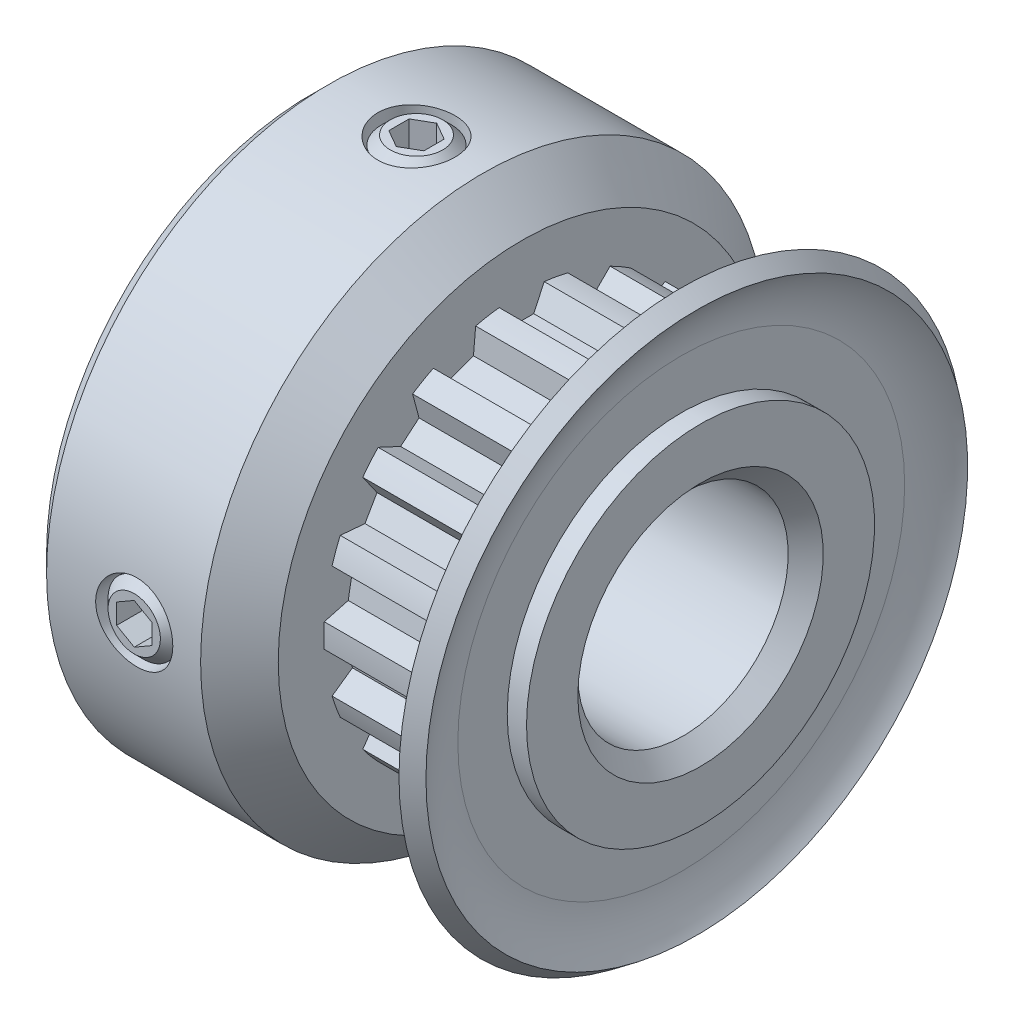
SolidWorks part; units mm, degrees
ref_plane "Front Plane" through (0, 0, 0) normal (0, 0, 1) x (1, 0, 0)
ref_plane "Top Plane" through (0, 0, 0) normal (0, 1, 0) x (1, 0, 0)
ref_plane "Right Plane" through (0, 0, 0) normal (1, 0, 0) x (0, 0, -1)
sketch "Sketch2" plane through (0, 0, 0) normal (1, 0, 0) x (0, 0, -1)
  line L3 (0, 0) -> (0, 4.9745) construction
  line L6 (0, -5.4825) -> (0, -5.8) construction
  line L7 (-0.5715, 5.4526) -> (-0.343, 4.9627)
  line L8 (0.5715, 5.4526) -> (0.343, 4.9627)
  line L9 (-0.5715, 5.4526) -> (-0.6423, 5.6046)
  line L10 (0.5715, 5.4526) -> (0.6423, 5.6046)
  line L12 (-0.343, 4.9627) -> (0.343, 4.9627)
  line L14 (0, 5.4825) -> (0, 5.8) construction
  line L15 (0, 0) -> (0, -1.143) construction
  circle A0 centre (0, 0) radius 5.8 construction
  circle A1 centre (0, 0) radius 4.9745 construction
  circle A2 centre (0, 0) radius 5.4825 construction
  arc A7 (0.6423, 5.6046) -> (-0.6423, 5.6046) centre (0, 0) ccw
  point P5 (0, 5.6412)
  dimension "D3" = 0.3175
  dimension "D1" = 50
sketch "Sketch1" plane through (0, 0, 0) normal (0, 0, 1) x (1, 0, 0)
  line L0 (-5.55, 0) -> (5.55, 0) construction
  line L1 (-5.55, 3) -> (5.55, 3)
  line L2 (-5.55, 3) -> (-5.55, 8.05)
  line L3 (-5.55, 8.05) -> (-0.657, 8.05)
  line L4 (-0.657, 8.05) -> (0.45, 6.943)
  line L5 (0.45, 6.943) -> (0.45, 5.8)
  line L6 (0.45, 5.8) -> (4.45, 5.8)
  line L7 (4.45, 5.8) -> (4.45, 6.3715)
  line L8 (4.45, 5.8) -> (5.55, 5.8) construction
  line L9 (5, 8.05) -> (5.55, 8.05)
  line L10 (5.55, 8.05) -> (5.55, 3)
  line L11 (5, 5.8) -> (5, 8.05) construction
  line L12 (-3.1035, 8.05) -> (-3.1035, 3) construction
  arc A0 (4.45, 6.3715) -> (5, 8.05) centre (7.2862, 6.3715) cw
  dimension "Bore Size" = 6
  dimension "Overall Width" = 11.1
  dimension "Inside Width" = 4
  dimension "Outside Width" = 5.1
  dimension "Hub Dia" = 16.1
  dimension "OD" = 16.1
  dimension "D1" = 45
  dimension "D2" = 11.6
  dimension "D3" = 1.143
  dimension "D4" = 0.5715
revolve "Revolve1" add sketch "Sketch1" angle 360 mid plane about L0
sketch "Sketch4" plane through (0.45, 0, 0) normal (1, 0, 0) x (0, 0, -1)
  circle A0 centre (0, 0) radius 5.6412
  circle A1 centre (0, 0) radius 5.8 construction
  circle A2 centre (0, 0) radius 5.8
extrude "Cut-Extrude2" cut sketch "Sketch4" along normal up to surface (4 mm away) up to face at (4.45, 0, 5.8)
sketch "Sketch3" plane through (0.45, 0, 0) normal (1, 0, 0) x (0, 0, -1)
  line L2 (-0.5715, 5.4526) -> (-0.343, 4.9627) construction
  line L3 (-0.343, 4.9627) -> (0.343, 4.9627) construction
  line L4 (0.5715, 5.4526) -> (0.343, 4.9627) construction
  line L5 (-0.6423, 5.6046) -> (-0.343, 4.9627)
  line L6 (-0.343, 4.9627) -> (0.343, 4.9627)
  line L7 (0.6423, 5.6046) -> (0.343, 4.9627)
  arc A1 (0.6423, 5.6046) -> (-0.6423, 5.6046) centre (0, 0) ccw construction
  arc A2 (0.6423, 5.6046) -> (-0.6423, 5.6046) centre (0, 0) ccw
extrude "Cut-Extrude1" cut sketch "Sketch3" along normal up to surface (4 mm away)
pattern_circular "CirPattern1" count 18 over 360 about axis through (0, 0, 0) along (1, 0, 0) of "Cut-Extrude1"
sketch "Sketch5" plane through (0, 0, 0) normal (0, 1, 0) x (1, 0, 0)
  line L0 (-5.55, 8.05) -> (-5.55, -8.05) construction
  line L1 (4.45, 6.3715) -> (4.45, -6.3715) construction
  line L2 (5.55, 8.05) -> (5.55, -8.05) construction
  line L3 (0.45, 6.943) -> (0.45, -6.943) construction
  line L4 (4.45, 6.3715) -> (4.45, -6.3715) construction
  line L5 (-5.55, 0) -> (5.55, 0) construction
  line L6 (-5.55, 0) -> (5.55, 0) construction
  point P0 (4.45, 0)
  point P14 (4.45, 0)
  point P15 (0.45, 0)
  dimension "D1" = 16.1
  dimension "D2" = 16.1
sketch "Sketch6" plane through (0, 0, 0) normal (0, 1, 0) x (1, 0, 0)
  line L0 (-5.55, 0) -> (-3.55, 0) construction
  line L1 (-5.55, 8.05) -> (-5.55, -8.05) construction
  line L2 (0.45, 0) -> (-1.55, 0) construction
  line L3 (0.45, -0.343) -> (0.45, 0.343) construction
  line L4 (-3.55, 0) -> (-2.55, 0) construction
  line L5 (-2.55, 0) -> (-3.2571, -0.7071) construction
  circle A0 centre (-2.55, 0) radius 1 construction
  circle A1 centre (-2.55, 0) radius 1.1
  point P13 (-3.2571, -0.7071)
  dimension "D1" = 0.1
  dimension "D2" = 45
  dimension "SS Dia" = 2
extrude "Cut-Extrude3" cut sketch "Sketch6" along normal through all
sketch "Sketch7" plane through (0, 0, 0) normal (0, 0, 1) x (1, 0, 0)
  line L0 (-3.296, 8.05) -> (-2.55, 8.05)
  line L1 (-3.55, 7.796) -> (-3.55, 3.635)
  line L2 (-3.55, 3.635) -> (-3.296, 3.381)
  line L3 (-3.296, 3.381) -> (-2.55, 3.381)
  line L4 (-2.55, 3.381) -> (-2.55, 8.05) construction
  line L6 (-3.55, 7.796) -> (-3.296, 8.05)
  line L7 (-5.55, 8.05) -> (-0.657, 8.05) construction
  line L8 (-2.55, 8.05) -> (-2.55, 3.381)
  point P0 (-3.55, 8.05)
  point P4 (-3.55, 3.381)
  dimension "D2" = 0.381
revolve "Revolve2" add sketch "Sketch7" angle 360 mid plane about L4
sketch "Sketch8" plane through (0, 8.05, 0) normal (0, 1, 0) x (1, 0, 0)
  line L0 (-2.55, 0) -> (-3.55, 0) construction
  line L1 (-2.55, 0.5774) -> (-3.05, 0.2887)
  line L2 (-3.05, 0.2887) -> (-3.05, -0.2887)
  line L3 (-3.05, -0.2887) -> (-2.55, -0.5774)
  line L4 (-2.55, -0.5774) -> (-2.05, -0.2887)
  line L5 (-2.05, -0.2887) -> (-2.05, 0.2887)
  line L6 (-2.05, 0.2887) -> (-2.55, 0.5774)
  circle A0 centre (-2.55, 0) radius 0.5 construction
  point P13 (-3.05, 0)
extrude "Cut-Extrude4" cut sketch "Sketch8" against normal blind 1.016
pattern_circular "CirPattern2" count 2 over 90 about axis through (-5.55, 0, 0) along (-1, 0, 0) of "Cut-Extrude3"
pattern_circular "CirPattern3" count 2 over 90 about axis through (0, 0, 0) along (1, 0, 0) of bodies 107
chamfer "Chamfer1" distance 0.5 angle 45 3 edges at (-5.55, 0, 8.05) (-5.55, 0, 3) (5.55, 0, 3)
sketch "Sketch9" plane through (0, 0, 0) normal (0, 0, 1) x (1, 0, 0)
  line L0 (5.55, 4.9627) -> (5.55, 8.05)
  line L1 (5.55, 8.05) -> (5.55, 3) construction
  line L2 (5, 5.8) -> (5, 8.05) construction
  line L3 (5, 6.3715) -> (5, 4.9627)
  line L4 (5, 8.05) -> (5.1926, 8.3124)
  line L5 (5, 4.9627) -> (5.55, 4.9627)
  line L6 (5, 8.05) -> (5.4433, 7.7245)
  line L7 (5.1926, 8.3124) -> (5.55, 8.05)
  line L8 (0.45, 4.9627) -> (5.55, 4.9627) construction
  line L9 (-5.55, 0) -> (5.55, 0) construction
  line L10 (-5.55, 0) -> (5.55, 0) construction
  arc A0 (5, 8.05) -> (4.45, 6.3715) centre (7.2862, 6.3715) ccw construction
  arc A3 (5, 6.3715) -> (5.4433, 7.7245) centre (7.2862, 6.3715) cw
revolve "Cut-Revolve1" cut sketch "Sketch9" angle 360 about L0
equation "\"D3@Sketch2\" = (\"hs@Sketch2\"-\"ht@Sketch2\")/2"
equation "\"D2@Sketch1\" = \"PD@Sketch2\""
equation "\"D3@Sketch1\" = \"hs@Sketch2\""
equation "\"D4@Sketch1\" = \"D3@Sketch1\"/2"
equation "\"D1@Sketch5\"=\"Hub Dia@Sketch1\""
equation "\"D2@Sketch5\"=\"OD@Sketch1\""
